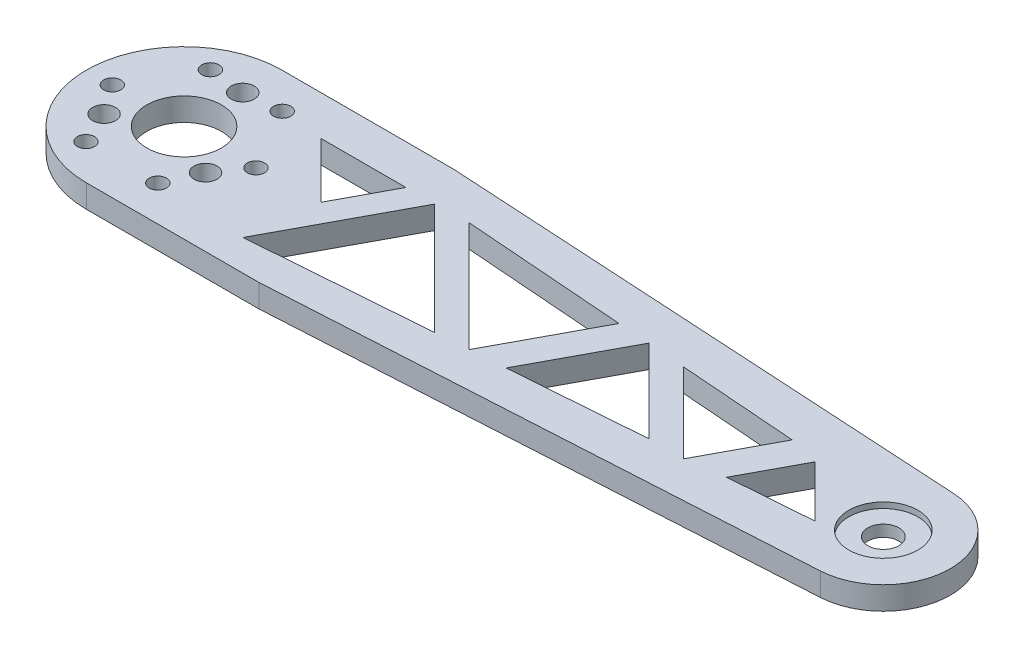
SolidWorks part; units mm, degrees
material "6061-O (SS)"
ref_plane "前视基准面" through (0, 0, 0) normal (0, 0, 1) x (1, 0, 0)
ref_plane "上视基准面" through (0, 0, 0) normal (0, 1, 0) x (1, 0, 0)
ref_plane "右视基准面" through (0, 0, 0) normal (1, 0, 0) x (0, 0, -1)
other "Configuration Table"
sketch "草图1" plane through (0, 0, 0) normal (0, 1, 0) x (1, 0, 0)
  line L0 (0, 0) -> (121.6825, 0) construction
  line L26 (33.5019, 10.0977) -> (52.8607, -9.2614)
  line L30 (73.1081, 7.8156) -> (87.5467, -6.6234)
  line L31 (79.7038, 7.2198) -> (93.5604, -6.637)
  line L32 (93.5604, -6.637) -> (100.1552, 5.6644)
  line L33 (100.0787, -5.6702) -> (105.4531, 4.3548)
  line L35 (105.4531, 4.3548) -> (114.3896, -4.5818)
  line L38 (0, 0) -> (0, 19.19) construction
  line L39 (0, 17) -> (30, 17)
  line L40 (0, -17) -> (30, -17)
  line L41 (30, 17) -> (122.3527, 11.6307)
  line L42 (30, -17) -> (122.3527, -11.6307)
  line L43 (39.3076, 10.2921) -> (67.5407, 8.1449)
  line L44 (58.4366, -8.8373) -> (67.5407, 8.1449)
  line L45 (39.3076, 10.2921) -> (58.4366, -8.8373)
  line L46 (21.8596, -11.6191) -> (33.5019, 10.0977)
  line L47 (21.8596, -11.6191) -> (52.8607, -9.2614)
  line L48 (13.7606, 10.0977) -> (28.5019, 10.0977)
  line L49 (64.4246, -8.3819) -> (87.5467, -6.6234)
  line L50 (64.4246, -8.3819) -> (73.1081, 7.8156)
  line L51 (79.7038, 7.2198) -> (100.1552, 5.6644)
  line L52 (23.3572, 0.501) -> (28.5019, 10.0977)
  line L53 (100.0787, -5.6702) -> (114.3896, -4.5818)
  line L54 (13.7606, 10.0977) -> (23.3572, 0.501)
  circle A2 centre (0, 0) radius 6.5
  circle A3 centre (121.6825, 0) radius 2.7
  arc A10 (122.3527, -11.6307) -> (122.3527, 11.6307) centre (121.6825, 0) ccw
  arc A11 (0, 17) -> (0, -17) centre (0, 0) ccw
  circle A13 centre (0, 0) radius 17 construction
  circle A14 centre (121.6825, 0) radius 11.65 construction
  point P5 (60.8413, 0)
  dimension "D1" = 121.6825
extrude "凸台-拉伸1" add sketch "草图1" along normal blind 4
sketch "草图4" plane through (0, 4, 0) normal (0, 1, 0) x (1, 0, 0)
  circle A0 centre (0, 10.2) radius 2
  circle A1 centre (8.8335, -5.1) radius 2
  circle A2 centre (-8.8335, -5.1) radius 2
  circle A3 centre (-6.25, 10.8253) radius 1.5
  circle A4 centre (6.25, 10.8253) radius 1.5
  circle A5 centre (12.5, 0) radius 1.5
  circle A6 centre (6.25, -10.8253) radius 1.5
  circle A7 centre (-6.25, -10.8253) radius 1.5
  circle A8 centre (-12.5, 0) radius 1.5
  point P8 (0, 0)
  point P22 (0, 0)
  dimension "D1" = 3
  dimension "D2" = 6
extrude "切除-拉伸4" cut sketch "草图4" against normal through all
sketch "草图5" plane through (0, 0, 0) normal (0, -1, 0) x (1, 0, 0)
  circle A0 centre (121.6825, 0) radius 6.01
extrude "切除-拉伸5" cut sketch "草图5" against normal blind 1
sketch "草图6" plane through (0, 4, 0) normal (0, 1, 0) x (1, 0, 0)
  circle A0 centre (121.6825, 0) radius 6.01
extrude "切除-拉伸6" cut sketch "草图6" against normal blind 1
